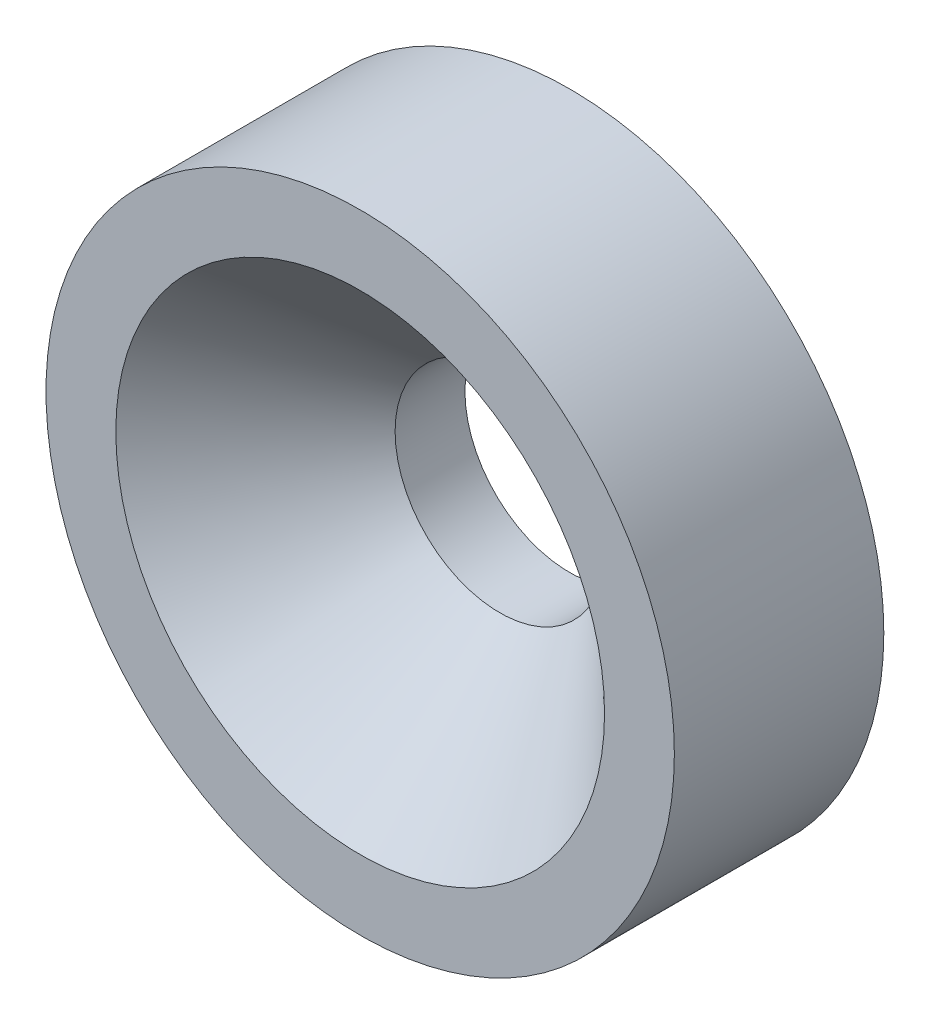
SolidWorks part; units mm, degrees
ref_plane "前视基准面" through (0, 0, 0) normal (0, 0, 1) x (1, 0, 0)
ref_plane "上视基准面" through (0, 0, 0) normal (0, 1, 0) x (1, 0, 0)
ref_plane "右视基准面" through (0, 0, 0) normal (1, 0, 0) x (0, 0, -1)
other "Configuration Table"
sketch "草图1" plane through (0, 0, 0) normal (0, 0, 1) x (1, 0, 0)
  circle A0 centre (0, 0) radius 4.5
  circle A1 centre (0, 0) radius 1.5
  dimension "D1" = 9
  dimension "D2" = 3
extrude "凸台-拉伸1" add sketch "草图1" along normal blind 3
chamfer "倒角1" distance 2 1 edges at (1.5, 0, 3)
